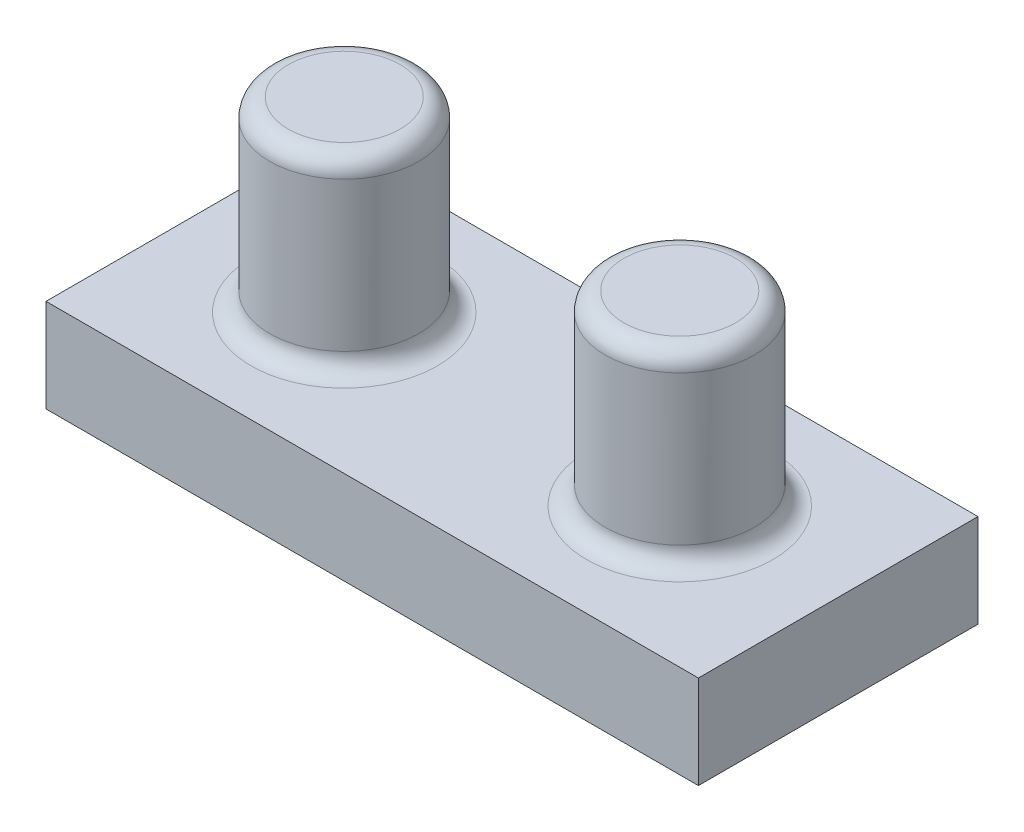
SolidWorks part; units mm, degrees
ref_plane "Front Plane" through (0, 0, 0) normal (0, 0, 1) x (1, 0, 0)
ref_plane "Top Plane" through (0, 0, 0) normal (0, 1, 0) x (1, 0, 0)
ref_plane "Right Plane" through (0, 0, 0) normal (1, 0, 0) x (0, 0, -1)
sketch "Sketch1" plane through (0, 0, 0) normal (0, 1, 0) x (1, 0, 0)
  line L0 (34.9998, 7.1697) -> (-26.696, 7.1697) construction
  circle A0 centre (7.0867, 7.1697) radius 4
  circle A1 centre (-10.9133, 7.1697) radius 4
  point P6 (0, 0)
  dimension "D1" = 18
  dimension "D2" = 8
  dimension "D3" = 8
extrude "Boss-Extrude1" add sketch "Sketch1" along normal blind 10
sketch "Sketch2" plane through (0, 0, 0) normal (0, -1, 0) x (-1, 0, 0)
  line L1 (19.4133, -0.3303) -> (-15.5867, -0.3303)
  line L2 (19.4133, -0.3303) -> (19.4133, 14.6697)
  line L3 (19.4133, 14.6697) -> (-15.5867, 14.6697)
  line L4 (-15.5867, -0.3303) -> (-15.5867, 14.6697)
  circle A0 centre (10.9133, 7.1697) radius 4 construction
  dimension "D1" = 35
  dimension "D2" = 8.5
  dimension "D3" = 15
  dimension "D4" = 7.5
extrude "Boss-Extrude2" add sketch "Sketch2" along normal blind 5
fillet "Fillet1" radius 1 4 edges at (-10.9133, 0, -11.1697) (7.0867, 0, -3.1697) (-10.9133, 10, -3.1697) (7.0867, 10, -3.1697)
sketch "Sketch3" plane through (0, 0, -14.6697) normal (0, 0, -1) x (-1, 0, 0)
  line L0 (15.3805, -4.4112) -> (-14.2204, -4.4112) construction
  text T0 "18 mm"
extrude "Cut-Extrude1" cut sketch "Sketch3" against normal blind 1
